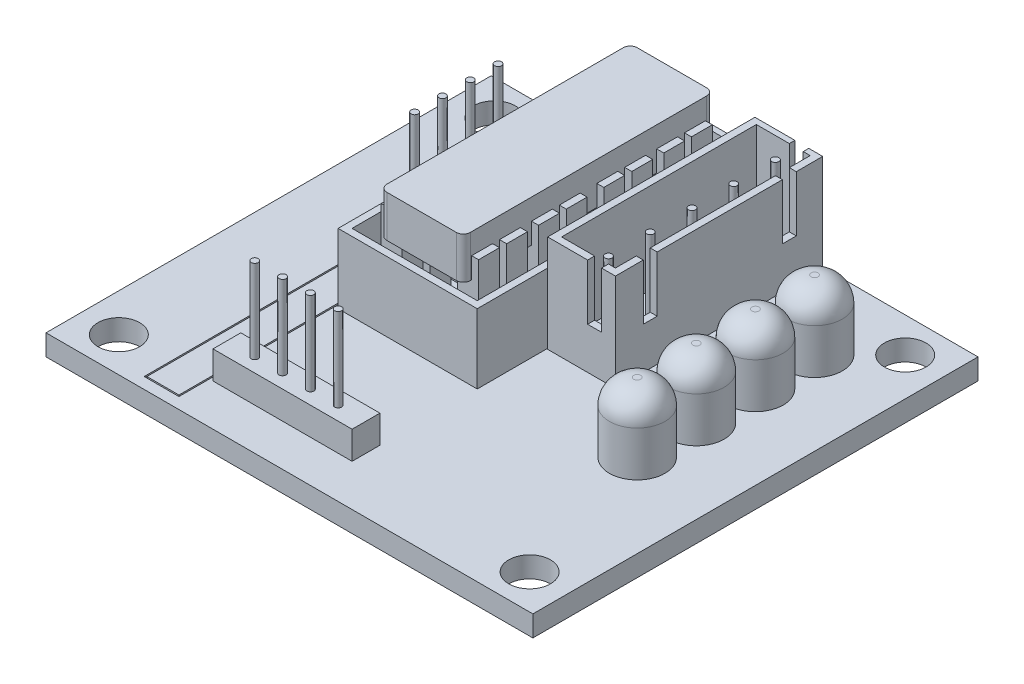
SolidWorks part; units mm, degrees
ref_plane "Ön Düzlem" through (0, 0, 0) normal (0, 0, 1) x (1, 0, 0)
ref_plane "Üst Düzlem" through (0, 0, 0) normal (0, 1, 0) x (1, 0, 0)
ref_plane "Sağ Düzlem" through (0, 0, 0) normal (1, 0, 0) x (0, 0, -1)
sketch "Çizim1" plane through (0, 0, 0) normal (0, 1, 0) x (1, 0, 0)
  line L0 (0, 0) -> (0, 16) construction
  line L1 (-17.5, 16) -> (17.5, 16)
  line L2 (-17.5, 16) -> (-17.5, -16)
  line L3 (-17.5, -16) -> (17.5, -16)
  line L4 (17.5, 16) -> (17.5, -16)
  line L5 (-17.5, 16) -> (17.5, -16) construction
  line L6 (-17.5, -16) -> (17.5, 16) construction
  line L7 (0, 16) -> (0, 0) construction
  line L8 (0, 0) -> (17.5, 0) construction
  circle A0 centre (-14.7656, 13.5) radius 1.5
  circle A1 centre (-14.7656, -13.5) radius 1.5
  circle A2 centre (14.7656, -13.5) radius 1.5
  circle A3 centre (14.7656, 13.5) radius 1.5
  point P0 (0, 0)
  dimension "D3" = 3
  dimension "D1" = 32
  dimension "D2" = 35
  dimension "D4" = 2.5
extrude "Yükseklik-Ekstrüzyon1" add sketch "Çizim1" along normal blind 1.5
sketch "Çizim2" plane through (0, 1.5, 0) normal (0, 1, 0) x (1, 0, 0)
  line L0 (-3.5, 16) -> (-3.5, -16) construction
  line L1 (17.5, 16) -> (-17.5, 16) construction
  line L2 (-17.5, -16) -> (17.5, -16) construction
  line L3 (-17.5, 16) -> (-17.5, -16) construction
  line L5 (-8.5, 16) -> (1.5, 16)
  line L6 (-8.5, 16) -> (-8.5, -4)
  line L7 (-8.5, -4) -> (1.5, -4)
  line L8 (1.5, 16) -> (1.5, -4)
  line L9 (-8.5, 16) -> (1.5, -4) construction
  line L10 (-8.5, -4) -> (1.5, 16) construction
  line L11 (-8, 15.5) -> (1, 15.5)
  line L12 (-8, 15.5) -> (-8, -3.5)
  line L13 (-8, -3.5) -> (1, -3.5)
  line L14 (1, 15.5) -> (1, -3.5)
  line L15 (-8, 15.5) -> (1, -3.5) construction
  line L16 (-8, -3.5) -> (1, 15.5) construction
  point P8 (-3.5, 6)
  point P9 (-3.5, 6)
  point P14 (-3.5, 6)
  dimension "D1" = 14
  dimension "D2" = 10
  dimension "D3" = 20
  dimension "D4" = 10
  dimension "D5" = 0.5
  dimension "D6" = 0.5
extrude "Yükseklik-Ekstrüzyon2" add sketch "Çizim2" along normal blind 5
sketch "Çizim3" plane through (0, 1.5, 0) normal (0, 1, 0) x (1, 0, 0)
  line L0 (4, 16) -> (4, -16) construction
  line L1 (17.5, 16) -> (1.5, 16) construction
  line L2 (-17.5, -16) -> (17.5, -16) construction
  line L3 (1.5, -4) -> (1.5, 16) construction
  line L5 (1.5641, 16) -> (6.4359, 16)
  line L6 (1.5641, 16) -> (1.5641, 1)
  line L7 (1.5641, 1) -> (6.4359, 1)
  line L8 (6.4359, 16) -> (6.4359, 1)
  line L9 (1.5641, 16) -> (6.4359, 1) construction
  line L10 (1.5641, 1) -> (6.4359, 16) construction
  line L11 (2.0641, 15.5) -> (5.9359, 15.5)
  line L12 (2.0641, 15.5) -> (2.0641, 1.5)
  line L13 (2.0641, 1.5) -> (5.9359, 1.5)
  line L14 (5.9359, 15.5) -> (5.9359, 1.5)
  line L15 (2.0641, 15.5) -> (5.9359, 1.5) construction
  line L16 (2.0641, 1.5) -> (5.9359, 15.5) construction
  point P8 (4, 8.5)
  point P9 (4, 8.5)
  point P14 (4, 8.5)
  dimension "D1" = 2.5
  dimension "D2" = 7.5
  dimension "D3" = 15
  dimension "D4" = 0.5
  dimension "D5" = 0.5
extrude "Yükseklik-Ekstrüzyon3" add sketch "Çizim3" along normal blind 7
sketch "Çizim4" plane through (0, 8.5, 0) normal (0, 1, 0) x (1, 0, 0)
  line L0 (5.9359, 8.5) -> (6.4359, 8.5) construction
  line L1 (5.9359, 1.5) -> (5.9359, 15.5) construction
  line L2 (6.4359, 1) -> (6.4359, 16) construction
  line L3 (6.1859, 8.5) -> (6.1859, 16) construction
  line L4 (6.4359, 16) -> (1.5641, 16) construction
  line L5 (5.9359, 4) -> (6.4359, 4)
  line L6 (5.9359, 14) -> (6.4359, 14)
  line L7 (5.9359, 14) -> (5.9359, 13)
  line L8 (5.9359, 13) -> (6.4359, 13)
  line L9 (6.4359, 14) -> (6.4359, 13)
  line L10 (5.9359, 14) -> (6.4359, 13) construction
  line L11 (5.9359, 13) -> (6.4359, 14) construction
  line L12 (6.4359, 3) -> (6.4359, 4)
  line L13 (5.9359, 3) -> (6.4359, 3)
  line L14 (5.9359, 3) -> (5.9359, 4)
  line L15 (4, 16) -> (4, 15.5) construction
  line L16 (5.9359, 15.5) -> (2.0641, 15.5) construction
  line L17 (4, 15.5) -> (4, 15.75) construction
  line L18 (4, 15.75) -> (6.4359, 15.75) construction
  line L19 (4.4359, 1.5) -> (5.4359, 1.5)
  line L20 (4.4359, 16) -> (5.4359, 16)
  line L21 (4.4359, 16) -> (4.4359, 15.5)
  line L22 (4.4359, 15.5) -> (5.4359, 15.5)
  line L23 (5.4359, 16) -> (5.4359, 15.5)
  line L24 (4.4359, 16) -> (5.4359, 15.5) construction
  line L25 (4.4359, 15.5) -> (5.4359, 16) construction
  line L26 (5.4359, 1) -> (5.4359, 1.5)
  line L27 (4.4359, 1) -> (5.4359, 1)
  line L28 (4.4359, 1) -> (4.4359, 1.5)
  point P10 (6.1859, 13.5)
  point P24 (4.9359, 15.75)
  dimension "D1" = 2
  dimension "D2" = 1
  dimension "D3" = 1
  dimension "D4" = 1
extrude "Kes-Ekstrüzyon1" cut sketch "Çizim4" against normal blind 4
sketch "Çizim5" plane through (0, 1.5, 0) normal (0, 1, 0) x (1, 0, 0)
  line L0 (4, 1.5) -> (4, 15.5) construction
  line L1 (2.0641, 1.5) -> (5.9359, 1.5) construction
  line L2 (5.9359, 15.5) -> (2.0641, 15.5) construction
  line L4 (2.0641, 15.5) -> (5.9359, 15.5)
  line L5 (2.0641, 15.5) -> (2.0641, 1.5)
  line L6 (2.0641, 1.5) -> (5.9359, 1.5)
  line L7 (5.9359, 15.5) -> (5.9359, 1.5)
  line L8 (2.0641, 15.5) -> (5.9359, 1.5) construction
  line L9 (2.0641, 1.5) -> (5.9359, 15.5) construction
  point P6 (4, 8.5)
extrude "Yükseklik-Ekstrüzyon4" add sketch "Çizim5" along normal blind 0.5
sketch "Çizim6" plane through (0, 2, 0) normal (0, 1, 0) x (1, 0, 0)
  line L0 (4.4359, 15.5) -> (4.4359, 1.5) construction
  line L1 (2.0641, 1.5) -> (5.9359, 1.5) construction
  circle A0 centre (4.4359, 8.5) radius 0.25
  circle A1 centre (4.4359, 11.5) radius 0.25
  circle A2 centre (4.4359, 14.5) radius 0.25
  circle A3 centre (4.4359, 5.5) radius 0.25
  circle A4 centre (4.4359, 2.5) radius 0.25
  dimension "D1" = 0.5
  dimension "D2" = 3
  dimension "D3" = 3
extrude "Yükseklik-Ekstrüzyon5" add sketch "Çizim6" along normal blind 6
sketch "Çizim7" plane through (0, 1.5, 0) normal (0, 1, 0) x (1, 0, 0)
  line L0 (-10, 16) -> (-10, -16) construction
  line L1 (-8.5, 16) -> (-17.5, 16) construction
  line L2 (-17.5, -16) -> (17.5, -16) construction
  line L3 (-8.5, 16) -> (-8.5, -4) construction
  line L5 (-9, 11) -> (-11, 11)
  line L6 (-9, 11) -> (-9, 1)
  line L7 (-9, 1) -> (-11, 1)
  line L8 (-11, 11) -> (-11, 1)
  line L9 (-9, 11) -> (-11, 1) construction
  line L10 (-9, 1) -> (-11, 11) construction
  point P8 (-10, 6)
  dimension "D1" = 1.5
  dimension "D2" = 10
  dimension "D3" = 2
  dimension "D4" = 5
extrude "Yükseklik-Ekstrüzyon6" add sketch "Çizim7" along normal blind 2
sketch "Çizim8" plane through (0, 3.5, 0) normal (0, 1, 0) x (1, 0, 0)
  line L0 (-10, 11) -> (-10, 1) construction
  line L1 (-9, 11) -> (-11, 11) construction
  line L2 (-11, 1) -> (-9, 1) construction
  line L3 (-10, 1) -> (-10, 6) construction
  line L4 (-10, 6) -> (-11, 6) construction
  line L5 (-11, 11) -> (-11, 1) construction
  circle A0 centre (-10, 7) radius 0.25
  circle A1 centre (-10, 9) radius 0.25
  circle A2 centre (-10, 3) radius 0.25
  circle A3 centre (-10, 5) radius 0.25
  dimension "D1" = 0.5
  dimension "D2" = 0.5
  dimension "D4" = 2
  dimension "D3" = 2
extrude "Yükseklik-Ekstrüzyon7" add sketch "Çizim8" along normal blind 6
sketch "Çizim9" plane through (0, 1.5, 0) normal (0, 1, 0) x (1, 0, 0)
  line L0 (-17.5, -12) -> (17.5, -12) construction
  line L1 (-17.5, 16) -> (-17.5, -16) construction
  line L2 (17.5, -16) -> (17.5, 16) construction
  line L3 (-17.5, -16) -> (17.5, -16) construction
  line L5 (-8.4957, -11) -> (1.5043, -11)
  line L6 (-8.4957, -11) -> (-8.4957, -13)
  line L7 (-8.4957, -13) -> (1.5043, -13)
  line L8 (1.5043, -11) -> (1.5043, -13)
  line L9 (-8.4957, -11) -> (1.5043, -13) construction
  line L10 (-8.4957, -13) -> (1.5043, -11) construction
  point P8 (-3.4957, -12)
  dimension "D1" = 4
  dimension "D2" = 10
  dimension "D3" = 2
extrude "Yükseklik-Ekstrüzyon8" add sketch "Çizim9" along normal blind 2
sketch "Çizim10" plane through (0, 3.5, 0) normal (0, 1, 0) x (1, 0, 0)
  line L0 (-8.4957, -12) -> (1.5043, -12) construction
  line L1 (-8.4957, -11) -> (-8.4957, -13) construction
  line L2 (1.5043, -13) -> (1.5043, -11) construction
  line L3 (1.5043, -12) -> (-3.4957, -12) construction
  line L4 (-3.4957, -12) -> (-3.4957, -11) construction
  line L5 (1.5043, -11) -> (-8.4957, -11) construction
  line L6 (-8.4957, -11) -> (-8.4957, -13) construction
  circle A0 centre (-4.4957, -12) radius 0.25
  circle A1 centre (-6.4957, -12) radius 0.25
  circle A2 centre (-2.4957, -12) radius 0.25
  circle A3 centre (-0.4957, -12) radius 0.25
  dimension "D1" = 0.5
  dimension "D2" = 0.5
  dimension "D4" = 2
  dimension "D3" = 2
extrude "Yükseklik-Ekstrüzyon9" add sketch "Çizim10" along normal blind 6
sketch "Çizim11" plane through (0, 1.5, 0) normal (0, 1, 0) x (1, 0, 0)
  line L0 (11.5, 16) -> (11.5, -16) construction
  line L1 (17.5, 16) -> (6.4359, 16) construction
  line L2 (-17.5, -16) -> (17.5, -16) construction
  line L3 (17.5, -16) -> (17.5, 16) construction
  circle A0 centre (11.5, 10.25) radius 2
  circle A1 centre (11.5, 6) radius 2
  circle A2 centre (11.5, 1.75) radius 2
  circle A3 centre (11.5, -2.5) radius 2
  point P8 (11.5, 10.25)
  point P9 (11.5, 6)
  point P10 (11.5, 1.75)
  point P11 (11.5, -2.5)
  dimension "D6" = 4
  dimension "D1" = 6
  dimension "D2" = 5.75
  dimension "D3" = 4.25
  dimension "D4" = 4.25
  dimension "D5" = 4.25
extrude "Kes-Ekstrüzyon2" cut sketch "Çizim11" against normal blind 0.02
sketch "Çizim13" plane through (0, 1.48, 0) normal (0, 1, 0) x (1, 0, 0)
  circle A0 centre (11.5, 10.25) radius 2
  circle A1 centre (11.5, 6) radius 2
  circle A2 centre (11.5, 1.75) radius 2
  circle A3 centre (11.5, -2.5) radius 2
extrude "Yükseklik-Ekstrüzyon10" add sketch "Çizim13" along normal blind 5
fillet "Radyus1" radius 1.75 4 edges at (11.5, 6.48, -8.25) (11.5, 6.48, -4) (11.5, 6.48, 0.25) (11.5, 6.48, 4.5)
sketch "Çizim14" plane through (0, 0, 0) normal (0, -1, 0) x (1, 0, 0)
  circle A0 centre (11.5, -10.25) radius 0.5
  circle A1 centre (11.5, -6) radius 0.5
  circle A2 centre (11.5, -1.75) radius 0.5
  circle A3 centre (11.5, 2.5) radius 0.5
  dimension "D1" = 1
extrude "Yükseklik-Ekstrüzyon11" add sketch "Çizim14" against normal blind 4
ref_plane "Düzlem2" through (0, 8, 0) normal (0, 1, 0) x (1, 0, 0)
sketch "Çizim15" plane through (0, 8, 0) normal (0, 1, 0) x (1, 0, 0)
  line L0 (-3.5, 15.5) -> (-3.5, -3.5) construction
  line L1 (1, 15.5) -> (-8, 15.5) construction
  line L2 (-8, -3.5) -> (1, -3.5) construction
  line L4 (-6, 15) -> (-1, 15)
  line L5 (-6.5, 14.5) -> (-6.5, -2.5)
  line L6 (-6, -3) -> (-1, -3)
  line L7 (-0.5, 14.5) -> (-0.5, -2.5)
  line L8 (-6.5, 15) -> (-0.5, -3) construction
  line L9 (-6.5, -3) -> (-0.5, 15) construction
  arc A0 (-6, 15) -> (-6.5, 14.5) centre (-6, 14.5) ccw
  arc A1 (-1, 15) -> (-0.5, 14.5) centre (-1, 14.5) cw
  arc A2 (-6.5, -2.5) -> (-6, -3) centre (-6, -2.5) ccw
  arc A3 (-1, -3) -> (-0.5, -2.5) centre (-1, -2.5) ccw
  point P6 (-3.5, 6)
  dimension "D3" = 0.5
  dimension "D1" = 18
  dimension "D2" = 6
extrude "Yükseklik-Ekstrüzyon12" add sketch "Çizim15" along normal blind 1.5 and the other way blind 1.5 separate body
sketch "Çizim16" plane through (0, 1.5, 0) normal (0, 1, 0) x (1, 0, 0)
  line L0 (-3.5, 15.5) -> (-3.5, -3.5) construction
  line L1 (1, 15.5) -> (-8, 15.5) construction
  line L2 (-8, -3.5) -> (1, -3.5) construction
  line L3 (-0.75, 15.5) -> (-0.75, -3.5) construction
  line L4 (-6.25, 15.5) -> (-6.25, -3.5) construction
  line L5 (-0.75, 6) -> (-6.25, 6) construction
  line L6 (-3.5, 6) -> (-3.5, 15) construction
  line L7 (-1.5, 8.1) -> (0, 8.1)
  line L8 (-1.5, 8.1) -> (-1.5, 6.6)
  line L9 (-1.5, 6.6) -> (0, 6.6)
  line L10 (0, 8.1) -> (0, 6.6)
  line L11 (-1.5, 8.1) -> (0, 6.6) construction
  line L12 (-1.5, 6.6) -> (0, 8.1) construction
  line L13 (-1, 15) -> (-6, 15) construction
  line L14 (-3.5, 15) -> (-3.5, 10.5) construction
  line L15 (-3.5, 10.5) -> (-0.75, 10.5) construction
  line L16 (-1.5, 14.4) -> (0, 14.4)
  line L17 (-1.5129, 10.1) -> (0.0129, 10.1)
  line L18 (-1.5129, 10.1) -> (-1.5129, 8.6)
  line L19 (-1.5129, 8.6) -> (0.0129, 8.6)
  line L20 (0.0129, 10.1) -> (0.0129, 8.6)
  line L21 (-1.5129, 10.1) -> (0.0129, 8.6) construction
  line L22 (-1.5129, 8.6) -> (0.0129, 10.1) construction
  line L23 (0, 12.9) -> (0, 14.4)
  line L24 (-1.5, 12.9) -> (0, 12.9)
  line L25 (-1.5, 12.9) -> (-1.5, 14.4)
  line L26 (-1.5129, 12.4) -> (0.0129, 12.4)
  line L27 (0.0129, 10.9) -> (0.0129, 12.4)
  line L28 (-1.5129, 10.9) -> (0.0129, 10.9)
  line L29 (-1.5129, 10.9) -> (-1.5129, 12.4)
  line L30 (-5.5, 6.6) -> (-7, 6.6)
  line L31 (-7, 8.1) -> (-7, 6.6)
  line L32 (-5.5, 8.1) -> (-7, 8.1)
  line L33 (-5.5, 8.1) -> (-5.5, 6.6)
  line L34 (-5.4871, 8.6) -> (-7.0129, 8.6)
  line L35 (-7.0129, 10.1) -> (-7.0129, 8.6)
  line L36 (-5.4871, 10.1) -> (-7.0129, 10.1)
  line L37 (-5.4871, 10.1) -> (-5.4871, 8.6)
  line L38 (-5.4871, 10.9) -> (-5.4871, 12.4)
  line L39 (-5.4871, 10.9) -> (-7.0129, 10.9)
  line L40 (-7.0129, 10.9) -> (-7.0129, 12.4)
  line L41 (-5.4871, 12.4) -> (-7.0129, 12.4)
  line L42 (-5.5, 12.9) -> (-5.5, 14.4)
  line L43 (-5.5, 12.9) -> (-7, 12.9)
  line L44 (-7, 12.9) -> (-7, 14.4)
  line L45 (-5.5, 14.4) -> (-7, 14.4)
  line L46 (-5.5, -0.9) -> (-7, -0.9)
  line L47 (-7, -0.9) -> (-7, -2.4)
  line L48 (-5.5, -2.4) -> (-7, -2.4)
  line L49 (-5.5, -0.9) -> (-5.5, -2.4)
  line L50 (-5.4871, 1.1) -> (-7.0129, 1.1)
  line L51 (-7.0129, 1.1) -> (-7.0129, -0.4)
  line L52 (-5.4871, -0.4) -> (-7.0129, -0.4)
  line L53 (-5.4871, 1.1) -> (-5.4871, -0.4)
  line L54 (-5.4871, 1.9) -> (-5.4871, 3.4)
  line L55 (-5.4871, 1.9) -> (-7.0129, 1.9)
  line L56 (-7.0129, 1.9) -> (-7.0129, 3.4)
  line L57 (-5.4871, 3.4) -> (-7.0129, 3.4)
  line L58 (-5.5, 3.9) -> (-5.5, 5.4)
  line L59 (-5.5, 3.9) -> (-7, 3.9)
  line L60 (-7, 3.9) -> (-7, 5.4)
  line L61 (-5.5, 5.4) -> (-7, 5.4)
  line L62 (-1.5, 5.4) -> (0, 5.4)
  line L63 (0, 3.9) -> (0, 5.4)
  line L64 (-1.5, 3.9) -> (0, 3.9)
  line L65 (-1.5, 3.9) -> (-1.5, 5.4)
  line L66 (-1.5129, 3.4) -> (0.0129, 3.4)
  line L67 (0.0129, 1.9) -> (0.0129, 3.4)
  line L68 (-1.5129, 1.9) -> (0.0129, 1.9)
  line L69 (-1.5129, 1.9) -> (-1.5129, 3.4)
  line L70 (-1.5129, 1.1) -> (-1.5129, -0.4)
  line L71 (-1.5129, 1.1) -> (0.0129, 1.1)
  line L72 (0.0129, 1.1) -> (0.0129, -0.4)
  line L73 (-1.5129, -0.4) -> (0.0129, -0.4)
  line L74 (-1.5, -0.9) -> (-1.5, -2.4)
  line L75 (-1.5, -0.9) -> (0, -0.9)
  line L76 (0, -0.9) -> (0, -2.4)
  line L77 (-1.5, -2.4) -> (0, -2.4)
  point P12 (-0.75, 7.35)
  point P23 (-0.75, 9.35)
  dimension "D1" = 2.75
  dimension "D2" = 1.5
  dimension "D3" = 1.5
  dimension "D4" = 0.6
  dimension "D5" = 1.5
  dimension "D6" = 0.5
extrude "Yükseklik-Ekstrüzyon13" add sketch "Çizim16" along normal blind 6.5
sketch "Çizim17" plane through (0, 1.5, 0) normal (0, 1, 0) x (1, 0, 0)
  line L0 (-10, 11) -> (-10, 16) construction
  line L1 (-9, 11) -> (-11, 11) construction
  line L2 (-8.5, 16) -> (-17.5, 16) construction
  line L3 (-10, 16) -> (-10, -16) construction
  line L4 (-17.5, -16) -> (17.5, -16) construction
  line L6 (-11.25, 13.129) -> (-8.75, 13.129)
  line L7 (-11.25, 13.129) -> (-11.25, -15.1927)
  line L8 (-11.25, -15.1927) -> (-8.75, -15.1927)
  line L9 (-8.75, 13.129) -> (-8.75, -15.1927)
  line L10 (-11.25, 13.129) -> (-8.75, -15.1927) construction
  line L11 (-11.25, -15.1927) -> (-8.75, 13.129) construction
  line L12 (-11.15, 13.029) -> (-8.85, 13.029)
  line L13 (-11.15, 13.029) -> (-11.15, -15.0927)
  line L14 (-11.15, -15.0927) -> (-8.85, -15.0927)
  line L15 (-8.85, 13.029) -> (-8.85, -15.0927)
  line L16 (-11.15, 13.029) -> (-8.85, -15.0927) construction
  line L17 (-11.15, -15.0927) -> (-8.85, 13.029) construction
  point P9 (-10, -1.0319)
  point P14 (-10, -1.0319)
  dimension "D1" = 2.5
  dimension "D2" = 0.1
  dimension "D3" = 0.1
extrude "Kes-Ekstrüzyon3" cut sketch "Çizim17" against normal blind 0.1
sketch "Çizim19" plane through (0, 0, -16) normal (0, 0, -1) x (-1, 0, 0)
  line L1 (-1.5, 6.5) -> (8.5, 6.5)
  line L2 (-1.5, 6.5) -> (-1.5, 1.5)
  line L3 (-1.5, 1.5) -> (8.5, 1.5)
  line L4 (8.5, 6.5) -> (8.5, 1.5)
extrude "Kes-Ekstrüzyon5" cut sketch "Çizim19" against normal blind 0.1
sketch "Çizim20" plane through (0, 0, -16) normal (0, 0, -1) x (-1, 0, 0)
  line L1 (-6.4359, 8.5) -> (-1.5641, 8.5)
  line L2 (-6.4359, 8.5) -> (-6.4359, 1.5)
  line L3 (-6.4359, 1.5) -> (-1.5641, 1.5)
  line L4 (-1.5641, 8.5) -> (-1.5641, 1.5)
extrude "Kes-Ekstrüzyon6" cut sketch "Çizim20" against normal blind 0.1
